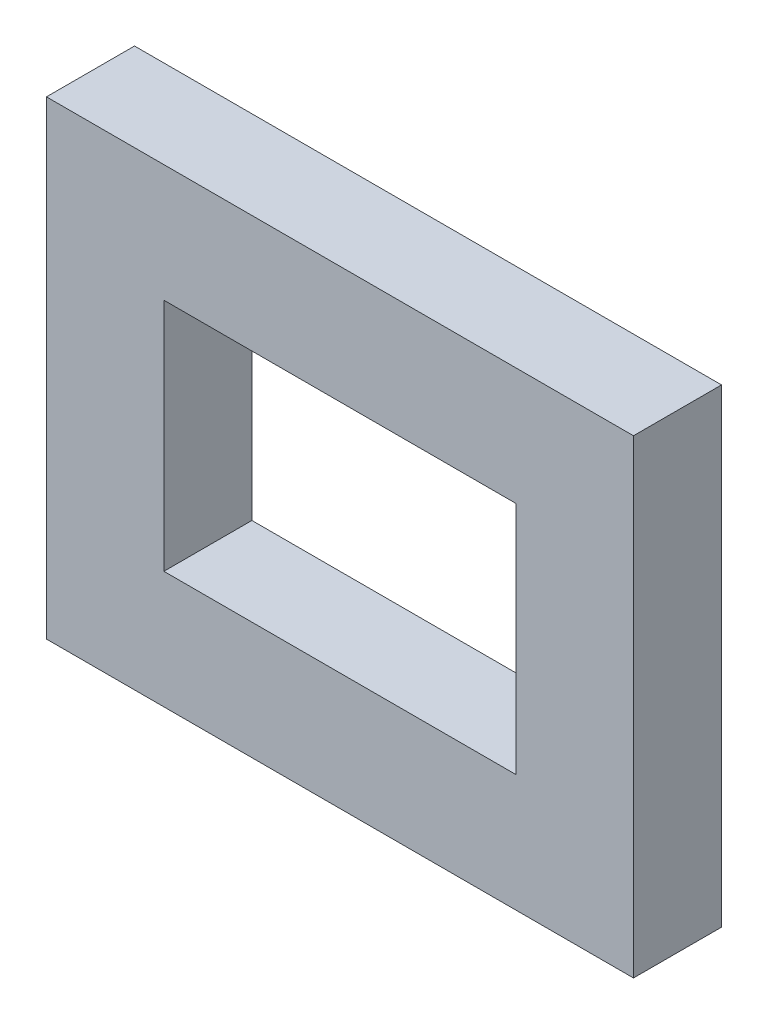
SolidWorks part; units mm, degrees
ref_plane "Front Plane" through (0, 0, 0) normal (0, 0, 1) x (1, 0, 0)
ref_plane "Top Plane" through (0, 0, 0) normal (0, 1, 0) x (1, 0, 0)
ref_plane "Right Plane" through (0, 0, 0) normal (1, 0, 0) x (0, 0, -1)
sketch "Sketch1" plane through (0, 0, 0) normal (0, 0, 1) x (1, 0, 0)
  line L1 (0, 0) -> (20, 0)
  line L2 (0, 0) -> (0, 16)
  line L3 (0, 16) -> (20, 16)
  line L4 (20, 0) -> (20, 16)
  line L6 (4, 4) -> (16, 4)
  line L7 (4, 4) -> (4, 12)
  line L8 (4, 12) -> (16, 12)
  line L9 (16, 4) -> (16, 12)
  dimension "D1" = 4
  dimension "D2" = 16
  dimension "D3" = 20
  dimension "D4" = 4
  dimension "D5" = 12
  dimension "D6" = 16
extrude "Profile" add sketch "Sketch1" along normal blind 3
equation "\"Profile_Depth\"= 3mm"
equation "\"D1@Profile\" = \"Profile_Depth\""
equation "\"Profile_Sketch_1\"= 4mm"
equation "\"D1@Sketch1\" = \"Profile_Sketch_1\""
equation "\"Profile_Sketch_2\"= 16mm"
equation "\"D2@Sketch1\" = \"Profile_Sketch_2\""
equation "\"Profile_Sketch_3\"= 20mm"
equation "\"D3@Sketch1\" = \"Profile_Sketch_3\""
equation "\"Profile_Sketch_4\"= 4mm"
equation "\"D4@Sketch1\" = \"Profile_Sketch_4\""
equation "\"Profile_Sketch_5\"= 12mm"
equation "\"D5@Sketch1\" = \"Profile_Sketch_5\""
equation "\"Profile_Sketch_6\"= 16mm"
equation "\"D6@Sketch1\" = \"Profile_Sketch_6\""
equation "\"EnvelopeWidth\"= 20mm"
equation "\"EnvelopeHeight\"= 16mm"
